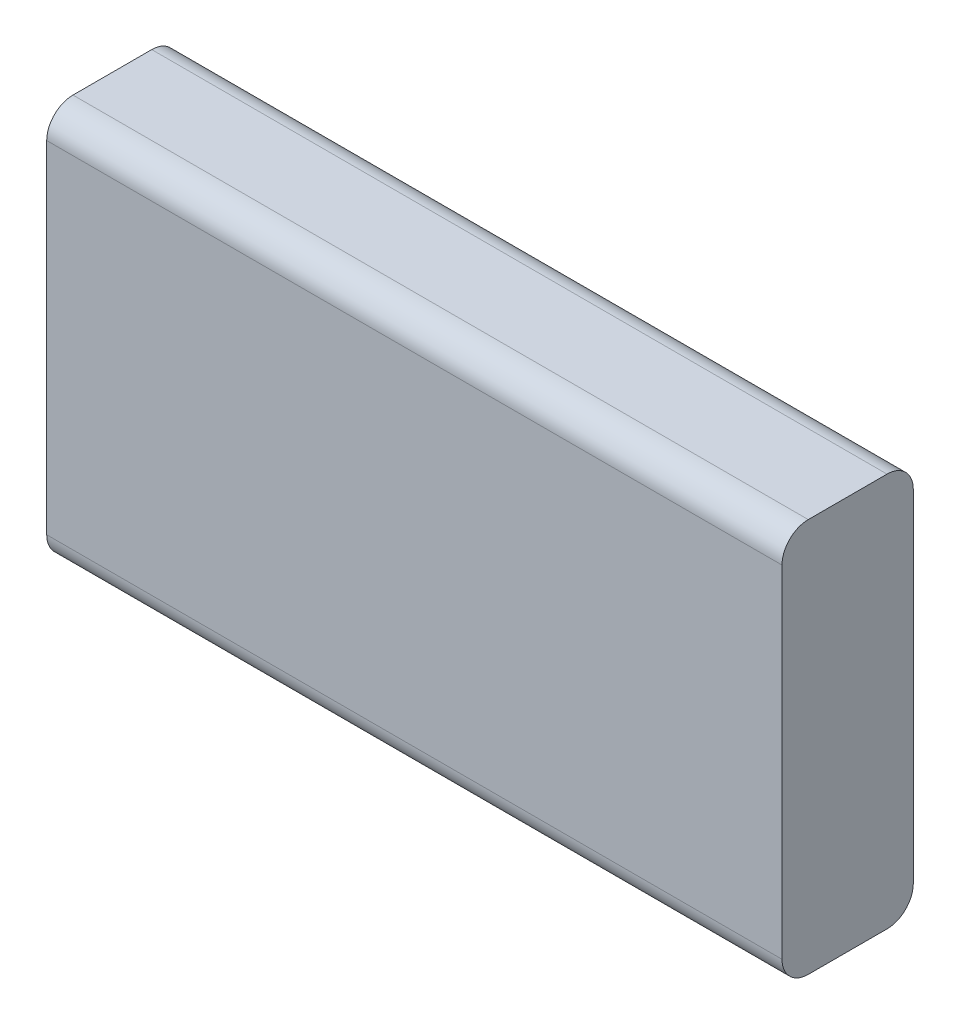
SolidWorks part; units mm, degrees
ref_plane "Ebene vorne" through (0, 0, 0) normal (0, 0, 1) x (1, 0, 0)
ref_plane "Ebene oben" through (0, 0, 0) normal (0, 1, 0) x (1, 0, 0)
ref_plane "Ebene rechts" through (0, 0, 0) normal (1, 0, 0) x (0, 0, -1)
sketch "Skizze1" plane through (0, 0, 0) normal (0, 0, 1) x (1, 0, 0)
  line L1 (0, 0) -> (56, 0)
  line L2 (0, 0) -> (0, 30)
  line L3 (0, 30) -> (56, 30)
  line L4 (56, 0) -> (56, 30)
  dimension "D1" = 30
  dimension "D2" = 56
extrude "Aufsatz-Linear austragen1" add sketch "Skizze1" along normal blind 10
fillet "Verrundung1" radius 2 4 edges at (28, 0, 10) (28, 0, 0) (28, 30, 0) (28, 30, 10)
